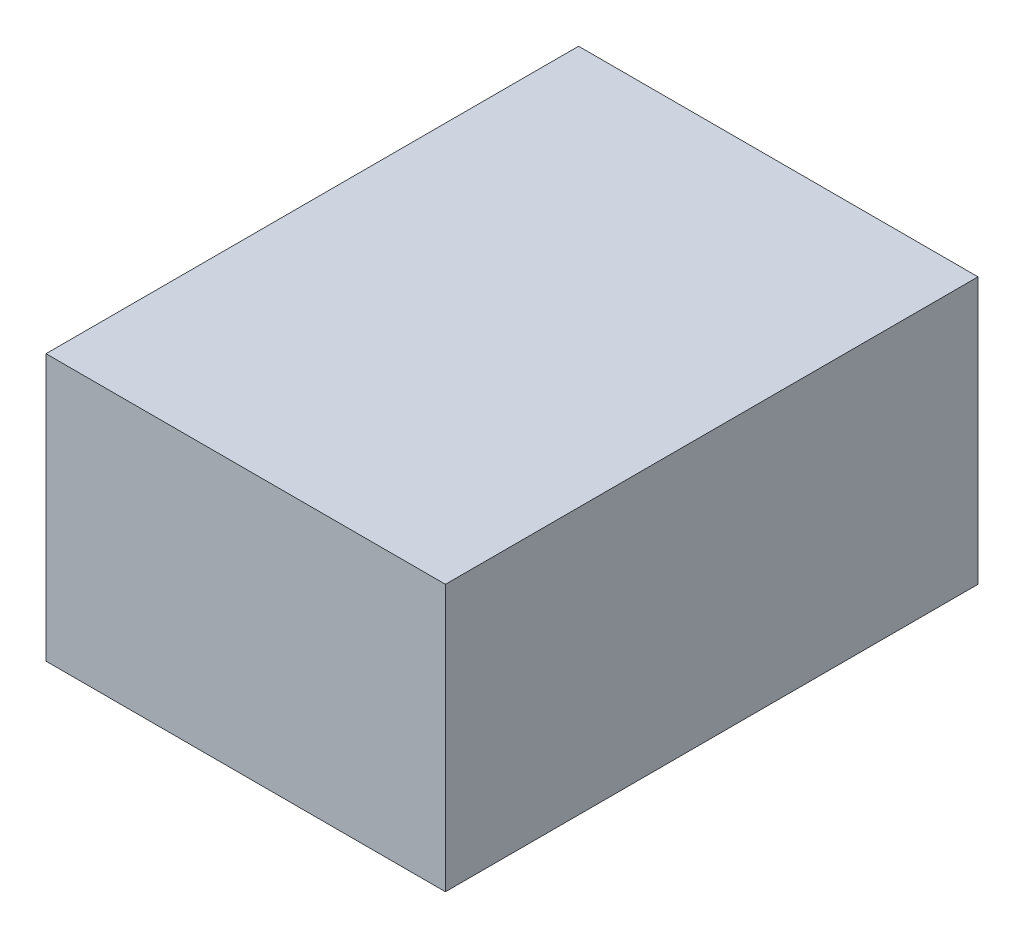
SolidWorks part; units mm, degrees
ref_plane "前视基准面" through (0, 0, 0) normal (0, 0, 1) x (1, 0, 0)
ref_plane "上视基准面" through (0, 0, 0) normal (0, 1, 0) x (1, 0, 0)
ref_plane "右视基准面" through (0, 0, 0) normal (1, 0, 0) x (0, 0, -1)
sketch "草图1" plane through (0, 0, 0) normal (0, 0, 1) x (1, 0, 0)
  line L1 (150, -100) -> (-150, -100)
  line L2 (150, -100) -> (150, 100)
  line L3 (150, 100) -> (-150, 100)
  line L4 (-150, -100) -> (-150, 100)
  line L5 (150, -100) -> (-150, 100) construction
  line L6 (150, 100) -> (-150, -100) construction
  point P0 (0, 0)
  dimension "D1" = 300
  dimension "D2" = 200
extrude "凸台-拉伸1" add sketch "草图1" along normal mid plane 400
sketch "草图2" plane through (-150, 0, 0) normal (-1, 0, 0) x (0, 0, 1)
  line L0 (-200, -30) -> (200, -30) construction
  line L1 (-200, 100) -> (-200, -100) construction
  line L2 (200, 100) -> (200, -100) construction
  text T0 "控制柜" font "Century Gothic" height 50
  dimension "D1" = 30
extrude "切除-拉伸1" cut sketch "草图2" against normal blind 1
